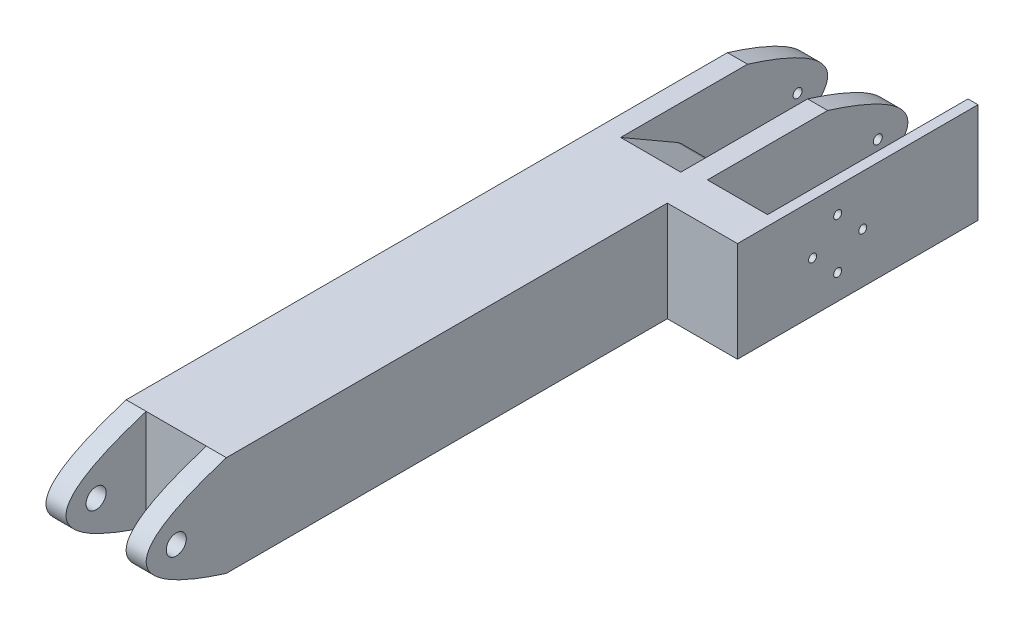
SolidWorks part; units mm, degrees
ref_plane "Front Plane" through (0, 0, 0) normal (0, 0, 1) x (1, 0, 0)
ref_plane "Top Plane" through (0, 0, 0) normal (0, 1, 0) x (1, 0, 0)
ref_plane "Right Plane" through (0, 0, 0) normal (1, 0, 0) x (0, 0, -1)
sketch "Sketch1" plane through (0, 0, 0) normal (1, 0, 0) x (0, 0, -1)
  line L0 (-255.8715, 42.046) -> (44.1285, 42.046)
  line L3 (-255.8715, -7.954) -> (44.1285, -7.954)
  circle A0 centre (-280.8715, 17.046) radius 5
  circle A1 centre (69.1285, 17.046) radius 2.25
  spline S0 degree 2 poles (44.1285, 42.046) (124.1285, 17.046) (44.1285, -7.954) knots 0 0 0 1 1 1
  spline S1 degree 2 poles (-255.8715, 42.046) (-335.8715, 17.046) (-255.8715, -7.954) knots 0 0 0 1 1 1
  dimension "D6" = 40
  dimension "D8" = 10
  dimension "D9" = 15
  dimension "D10" = 4.5
  dimension "D1" = 300
  dimension "D2" = 50
  dimension "D3" = 25
  dimension "D4" = 40
  dimension "D5" = 15
  dimension "D7" = 0
extrude "Boss-Extrude1" add sketch "Sketch1" along normal blind 50
sketch "Sketch2" plane through (0, 0, 0) normal (0, 1, 0) x (1, 0, 0)
  line L0 (50, 84.1285) -> (0, 84.1285) construction
  line L1 (10, 84.1285) -> (40, 84.1285)
  line L2 (10, 84.1285) -> (10, 24.1285)
  line L3 (10, 24.1285) -> (40, 24.1285)
  line L4 (40, 84.1285) -> (40, 24.1285)
  line L6 (0, 84.1285) -> (0, 44.1285) construction
  dimension "D1" = 10
  dimension "D2" = 10
  dimension "D3" = 60
extrude "Cut-Extrude1" cut sketch "Sketch2" along normal blind 52 and the other way blind 35
sketch "Sketch3" plane through (0, -7.954, 0) normal (0, -1, 0) x (1, 0, 0)
  line L0 (50, 295.8715) -> (0, 295.8715) construction
  line L1 (10, 295.8715) -> (40, 295.8715)
  line L2 (10, 295.8715) -> (10, 255.8715)
  line L3 (10, 255.8715) -> (40, 255.8715)
  line L4 (40, 295.8715) -> (40, 255.8715)
  line L5 (50, 255.8715) -> (0, 255.8715) construction
  dimension "D1" = 10
  dimension "D2" = 10
extrude "Cut-Extrude2" cut sketch "Sketch3" against normal blind 52
sketch "Sketch4" plane through (0, 0, 0) normal (-1, 0, 0) x (0, 0, 1)
  line L1 (-44.1285, 42.046) -> (255.8715, 42.046) construction
  line L5 (-24.1285, 17.046) -> (-24.1285, 42.046)
  line L6 (-24.1285, 42.046) -> (19.1728, 42.046)
  line L7 (-24.1285, 17.046) -> (19.1728, 42.046)
  line L8 (-24.1285, -7.954) -> (-24.1285, 42.046) construction
  dimension "D1" = 25
  dimension "D2" = 60
  dimension "D3" = 0
extrude "Cut-Extrude3" cut sketch "Sketch4" against normal blind 30 from offset 10 offset against normal yes
sketch "Sketch5" plane through (0, 0, 0) normal (-1, 0, 0) x (0, 0, 1)
  line L0 (-24.1285, -7.954) -> (-24.1285, 17.046)
  line L1 (-24.1285, 17.046) -> (19.1728, -7.954)
  line L2 (255.8715, -7.954) -> (-44.1285, -7.954) construction
  line L3 (19.1728, -7.954) -> (-24.1285, -7.954)
  line L5 (-24.1285, -7.954) -> (-24.1285, 17.046) construction
  dimension "D1" = 25
  dimension "D2" = 60
  dimension "D3" = 0
extrude "Cut-Extrude4" cut sketch "Sketch5" against normal blind 30 from offset 10 offset against normal yes
sketch "Sketch6" plane through (0, 42.046, 0) normal (0, 1, 0) x (1, 0, 0)
  line L0 (50, -35.8715) -> (85, -35.8715)
  line L1 (50, 44.1285) -> (50, -255.8715) construction
  line L2 (85, -35.8715) -> (85, 84.1285)
  line L3 (85, 84.1285) -> (80, 84.1285)
  line L4 (80, 84.1285) -> (80, -15.8715)
  line L5 (80, -15.8715) -> (50, -15.8715)
  line L9 (50, 84.1285) -> (40, 84.1285) construction
  line L20 (40, 44.1285) -> (40, -19.1728)
  line L21 (40, -19.1728) -> (10, -19.1728)
  line L22 (10, -19.1728) -> (10, 44.1285)
  line L23 (10, 44.1285) -> (0, 44.1285)
  line L24 (0, 44.1285) -> (0, -255.8715)
  line L25 (0, -255.8715) -> (10, -255.8715)
  line L26 (10, -255.8715) -> (40, -255.8715)
  line L27 (40, -255.8715) -> (50, -255.8715)
  line L28 (50, -255.8715) -> (50, 44.1285)
  line L29 (50, 44.1285) -> (40, 44.1285)
  line L38 (50, -35.8715) -> (50, -15.8715)
  dimension "D1" = 30
  dimension "D2" = 5
  dimension "D3" = 100
  dimension "D4" = 20
  dimension "D5" = 0
extrude "Boss-Extrude2" add sketch "Sketch6" against normal blind 50
sketch "Sketch7" plane through (85, 0, 0) normal (1, 0, 0) x (0, 0, -1)
  line L1 (-35.8715, 42.046) -> (84.1285, 42.046) construction
  line L2 (-35.8715, -7.954) -> (-35.8715, 42.046) construction
  circle A0 centre (14.1285, 17.046) radius 15
  dimension "D1" = 30
  dimension "D2" = 25
  dimension "D3" = 50
sketch "Sketch8" plane through (85, 0, 0) normal (1, 0, 0) x (0, 0, -1)
  circle A0 centre (14.1285, 29.546) radius 2
  circle A1 centre (14.1285, 17.046) radius 15 construction
  circle A2 centre (26.6285, 17.046) radius 2
  circle A3 centre (14.1285, 4.546) radius 2
  circle A4 centre (1.6285, 17.046) radius 2
  dimension "D2" = 4
  dimension "D1" = 12.5
  dimension "D3" = 12.5
  dimension "D4" = 12.5
  dimension "D5" = 12.5
extrude "Cut-Extrude5" cut sketch "Sketch8" against normal blind 10
fillet "Fillet1" radius 10 1 edges at (25, 17.046, -24.1285)
